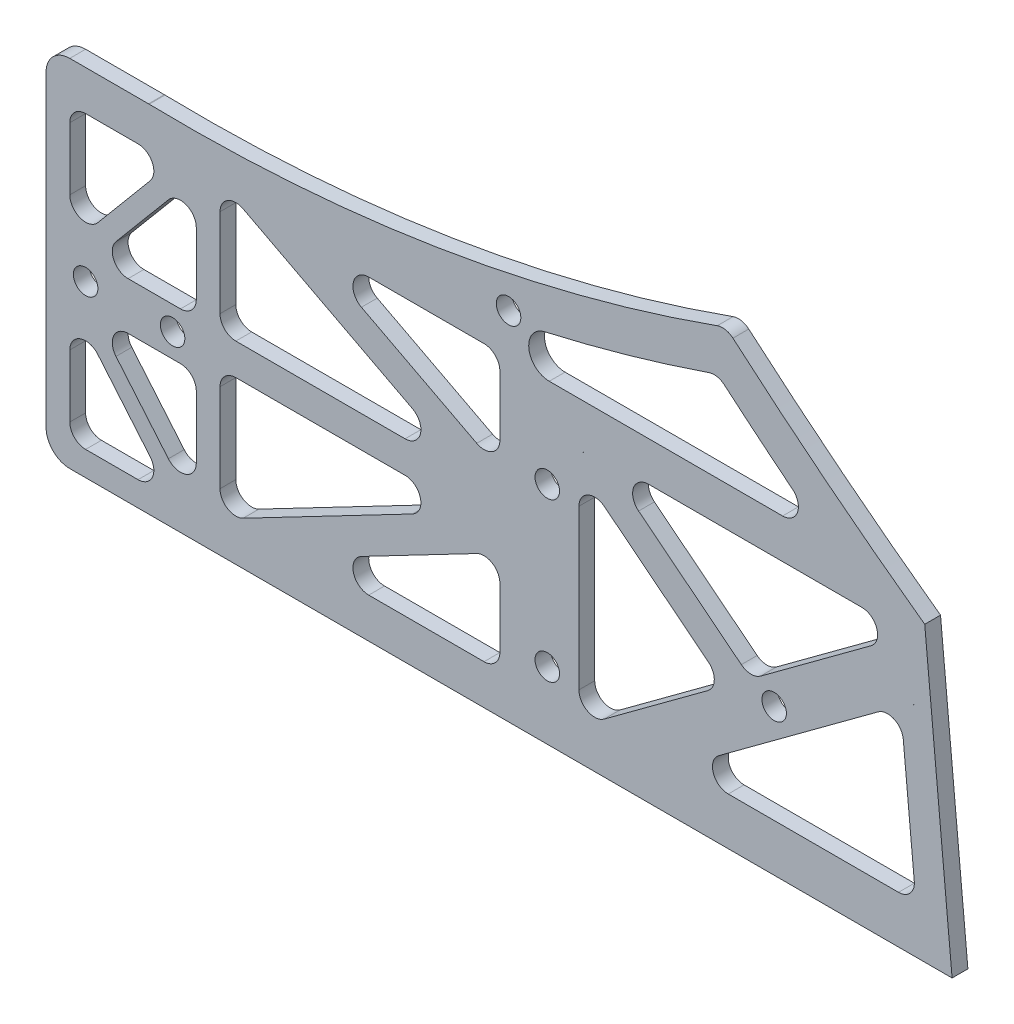
SolidWorks part; units mm, degrees
material "Thornel Mat VMA"
ref_plane "前视基准面" through (0, 0, 0) normal (0, 0, 1) x (1, 0, 0)
ref_plane "上视基准面" through (0, 0, 0) normal (0, 1, 0) x (1, 0, 0)
ref_plane "右视基准面" through (0, 0, 0) normal (1, 0, 0) x (0, 0, -1)
sketch "草图1" plane through (0, 0, 0) normal (0, 0, 1) x (1, 0, 0)
  line L1 (-82.5, -28.5) -> (82.5, -28.5)
  line L2 (-82.5, -28.5) -> (-82.5, 28.5)
  line L3 (-82.5, 28.5) -> (82.5, 28.5)
  line L4 (82.5, -28.5) -> (82.5, 28.5)
  line L5 (0, 28.5) -> (0, -28.5) construction
  line L6 (-82.5, 0) -> (82.5, 0) construction
  point P0 (0, 0)
  dimension "D1" = 57
  dimension "D2" = 165
extrude "凸台-拉伸1" add sketch "草图1" along normal blind 2
sketch "草图2" plane through (0, 0, 2) normal (0, 0, 1) x (1, 0, 0)
  line L0 (-82.5, 28.5) -> (-82.5, -28.5) construction
  line L1 (82.5, 28.5) -> (-82.5, 28.5) construction
  line L2 (82.5, -28.5) -> (82.5, 28.5) construction
  line L3 (-82.5, 16.5) -> (-82.5, 28.5)
  line L4 (-82.5, 28.5) -> (-7.5, 28.5)
  line L5 (-7.5, 28.5) -> (82.5, 28.5)
  line L6 (82.5, 28.5) -> (82.5, -28.5)
  arc A0 (-82.5, 16.5) -> (-7.5, 28.5) centre (-76.0232, 216.3951) ccw
  arc A1 (-7.5, 28.5) -> (82.5, -28.5) centre (222.5868, 292.2424) ccw
  dimension "D1" = 200
  dimension "D4" = 350
  dimension "D2" = 75
  dimension "D3" = 12
extrude "切除-拉伸1" cut sketch "草图2" against normal blind 6
sketch "草图3" [suppressed] plane through (0, 0, 41) normal (0, 0, 1) x (1, 0, 0)
  line L0 (-82.5, 16.5) -> (-82.5, -28.5) construction
  line L1 (-82.5, 13.4984) -> (-82.5, -28.5)
  line L2 (-82.5, -28.5) -> (72.8967, -28.5)
  line L3 (-82.5, -28.5) -> (82.5, -28.5) construction
  arc A2 (-82.5972, 13.5016) -> (-6.4722, 25.6816) centre (-76.0232, 216.3951) ccw
  arc A3 (-82.5, 13.4984) -> (-8.3642, 25.0021) centre (-76.0232, 216.3951) ccw
  arc A5 (-9.7222, 26.4846) -> (81.6278, -31.3704) centre (140.6454, 162.8612) ccw
  arc A6 (-8.3642, 25.0021) -> (72.8967, -28.5) centre (140.6454, 162.8612) ccw
  dimension "D1" = 3
  dimension "D2" = 3
extrude "切除-拉伸2" [suppressed] cut sketch "草图3" against normal blind 73
sketch "草图4" plane through (0, 0, 2) normal (0, 0, 1) x (1, 0, 0)
  line L0 (0, 0) -> (-77.5, 0) construction
  line L1 (-77.5, 0) -> (-77.5, -7) construction
  circle A1 centre (-77.5, -7) radius 1.55
  dimension "D3" = 3.1
  dimension "D1" = 77.5
  dimension "D2" = 7
extrude "切除-拉伸3" cut sketch "草图4" against normal blind 33
fillet "圆角1" [suppressed] radius 2
sketch "草图5" [suppressed] plane through (0, 0, 41) normal (0, 0, 1) x (1, 0, 0)
  circle A4 centre (-35, 16.5624) radius 4
  arc A6 (-82.5, 16.5) -> (-7.5, 28.5) centre (-76.0232, 216.3951) ccw construction
  dimension "D1" = 8
  dimension "D2" = 35
extrude "凸台-拉伸2" [suppressed] add sketch "草图5" against normal up to surface (41 mm away)
sketch "草图6" [suppressed] plane through (0, 0, 41) normal (0, 0, 1) x (1, 0, 0)
  circle A4 centre (40, -14.5832) radius 4
  arc A5 (-7.5, 28.5) -> (82.5, -28.5) centre (140.6454, 162.8612) ccw construction
  dimension "D1" = 8
  dimension "D2" = 40
extrude "凸台-拉伸3" [suppressed] add sketch "草图6" against normal up to surface (41 mm away)
sketch "草图7" [suppressed] plane through (0, 0, 0) normal (0, 0, -1) x (-1, 0, 0)
  circle A0 centre (35, 16.5624) radius 1.925
  circle A1 centre (-40, -14.5832) radius 1.925
  arc A2 (-43.8719, -15.5873) -> (-37.1511, -11.7753) centre (-40, -14.5832) ccw construction
  arc A3 (31.4241, 18.3549) -> (38.9929, 16.8011) centre (35, 16.5624) ccw construction
  dimension "D1" = 3.85
  dimension "D2" = 3.85
extrude "切除-拉伸4" [suppressed] cut sketch "草图7" against normal blind 50
sketch "草图8" plane through (0, 0, 2) normal (0, 0, 1) x (1, 0, 0)
  circle A0 centre (-1.4, -10) radius 1.55 construction
  circle A1 centre (-30.1, -20) radius 1.55 construction
  circle A2 centre (-30.1, 0) radius 1.55 construction
  circle A3 centre (-1.4, -10) radius 1.55
  circle A4 centre (-30.1, -20) radius 1.55
  circle A5 centre (-30.1, 0) radius 1.55
extrude "切除-拉伸5" cut sketch "草图8" against normal blind 10
fillet "圆角2" [suppressed] radius 3
chamfer "倒角1" [suppressed] distance 0.15 angle 45
sketch "草图9" plane through (0, 0, 0) normal (0, 0, -1) x (-1, 0, 0)
  circle A0 centre (-40, -14.5832) radius 2.075 construction
  circle A1 centre (35, 16.5624) radius 2.075 construction
  circle A2 centre (-40, -14.5832) radius 2.075 construction
  circle A3 centre (35, 16.5624) radius 2.075 construction
  circle A4 centre (35, 16.5624) radius 1.55
  circle A5 centre (-40, -14.5832) radius 1.55
  dimension "D1" = 3.1
extrude "切除-拉伸6" cut sketch "草图9" against normal blind 10
fillet "圆角3" radius 2 1 edges at (-7.5, 28.5, 1)
fillet "圆角4" radius 2 2 edges at (-82.5, -28.5, 1) (-82.5, 16.5, 1)
fillet "圆角5" [suppressed] radius 2
chamfer "倒角2" [suppressed] distance 1 angle 45
chamfer "倒角3" [suppressed] distance 1 angle 45
fillet "圆角6" [suppressed] radius 0.7
fillet "圆角7" [suppressed] radius 2
sketch "草图10" plane through (0, 0, 2) normal (0, 0, 1) x (1, 0, 0)
  line L1 (-29.8496, 11.3951) -> (5.4468, 11.3951)
  arc A0 (-80.4557, 16.4442) -> (-8.5997, 28.1026) centre (-76.0232, 216.3951) ccw construction
  arc A7 (-30.4279, 16.53) -> (-29.8496, 11.3951) centre (-29.8496, 13.9951) ccw
  arc A8 (-9.89, 23.9524) -> (80.4988, -33.082) centre (222.5868, 292.2424) ccw
  arc A9 (-8.5667, 22.8115) -> (5.4468, 11.3951) centre (222.5868, 292.2424) ccw
  arc A10 (-30.4279, 16.53) -> (-8.5667, 22.8115) centre (-76.0232, 216.3951) ccw
  dimension "D3" = 5.2
  dimension "D1" = 5
  dimension "D2" = 5
extrude "切除-拉伸7" cut sketch "草图10" against normal blind 10
fillet "圆角8" radius 2 2 edges at (5.4468, 11.3951, 1) (-8.5667, 22.8115, 1)
sketch "草图11" plane through (0, 0, 2) normal (0, 0, 1) x (1, 0, 0)
  line L0 (-71.5, 12.4442) -> (-71.5, -24.5)
  line L1 (-71.5, -24.5) -> (-36.1, -6.0279)
  line L2 (-36.1, -6.0279) -> (-71.5, 12.4442)
  line L3 (-36.1, -6.0279) -> (-71.5, -6.0279) construction
  line L4 (-80.5, -28.5) -> (82.5, -28.5) construction
  line L5 (-60.843, 11.3951) -> (-36.1, -1.5161)
  line L6 (-36.1, -1.5161) -> (-36.1, 11.3951)
  line L7 (-36.1, 11.3951) -> (-60.843, 11.3951)
  line L8 (-29.8496, 11.3951) -> (-0.3329, 11.3951) construction
  line L9 (-36.1, -4.0279) -> (-71.5, -4.0279)
  line L10 (-36.1, -8.0279) -> (-71.5, -8.0279)
  line L11 (-36.1, -4.0279) -> (-36.1, -8.0279)
  line L12 (-71.5, -4.0279) -> (-71.5, -8.0279)
  line L13 (-36.1, -10.5397) -> (-36.1, -23.4509)
  line L14 (-60.843, -23.4509) -> (-36.1, -10.5397)
  line L15 (-36.1, -23.4509) -> (-60.843, -23.4509)
  circle A1 centre (-77.5, -7) radius 1.55 construction
  circle A2 centre (-30.1, 0) radius 1.55 construction
  dimension "D2" = 4
  dimension "D3" = 6
  dimension "D1" = 4
  dimension "D4" = 6
  dimension "D5" = 4
  dimension "D6" = 2
  dimension "D7" = 2
extrude "切除-拉伸8" cut sketch "草图11" against normal blind 10 contours L15 L13 L14 | L1 L10 L0 | L9 L2 L0 | L6 L7 L5
fillet "圆角9" radius 2 12 edges at (-39.9328, -4.0279, 1) (-36.1, -10.5397, 1) (-36.1, -23.4509, 1) (-60.843, -23.4509, 1) (-36.1, -1.5161, 1) (-60.843, 11.3951, 1) (-36.1, 11.3951, 1) (-71.5, -24.5, 1) (-71.5, -8.0279, 1) (-39.9328, -8.0279, 1) (-71.5, -4.0279, 1) (-71.5, 12.4442, 1)
sketch "草图12" plane through (0, 0, 2) normal (0, 0, 1) x (1, 0, 0)
  line L0 (-26.1, 6.3951) -> (-26.1, -24.5)
  line L1 (-26.1, -24.5) -> (10.8729, 2.7859)
  line L2 (9.6853, 6.3951) -> (-26.1, 6.3951)
  line L3 (-29.8496, 11.3951) -> (-0.3329, 11.3951) construction
  line L4 (16.5197, -0.5038) -> (-13.2856, -22.5)
  line L5 (-13.2856, -22.5) -> (51.996, -22.5)
  line L6 (-80.5, -28.5) -> (82.5, -28.5) construction
  circle A0 centre (-30.1, 0) radius 1.55 construction
  circle A2 centre (-1.4, -10) radius 1.55 construction
  arc A3 (-6.6157, 27.7312) -> (82.5, -28.5) centre (222.5868, 292.2424) ccw construction
  arc A5 (10.8729, 2.7859) -> (9.6853, 6.3951) centre (9.6853, 4.3951) ccw
  arc A6 (16.5197, -0.5038) -> (51.996, -22.5) centre (222.5868, 292.2424) ccw
  dimension "D6" = 3
  dimension "D8" = 2
  dimension "D3" = 8
  dimension "D1" = 5
  dimension "D2" = 4
  dimension "D4" = 6
  dimension "D5" = 4
  dimension "D7" = 3
extrude "切除-拉伸9" cut sketch "草图12" against normal blind 10
fillet "圆角10" radius 2 5 edges at (-26.1, 6.3951, 1) (51.996, -22.5, 1) (16.5197, -0.5038, 1) (-13.2856, -22.5, 1) (-26.1, -24.5, 1)
sketch "草图13" plane through (0, 0, 2) normal (0, 0, 1) x (1, 0, 0)
  line L0 (-25.5142, 5.8093) -> (-6.0197, -9.6808) construction
  line L1 (-22.9124, -22.1476) -> (10.8729, 2.7859) construction
  line L6 (-26.7584, 4.2435) -> (-7.264, -11.2467)
  line L7 (-24.27, 7.3752) -> (-4.3529, -8.4508)
  line L8 (-26.7584, 4.2435) -> (-24.27, 7.3752)
  line L10 (-24.27, 7.3752) -> (-4.7755, -8.115) construction
  line L11 (-4.3529, -8.4508) -> (-7.264, -11.2467)
  arc A1 (-24.1, 6.3951) -> (-26.1, 4.3951) centre (-24.1, 4.3951) ccw construction
  dimension "D1" = 2
  dimension "D2" = 2
extrude "凸台-拉伸4" add sketch "草图13" against normal up to surface (2 mm away) up to face at (23.4152, -14.3272, 0)
fillet "圆角11" radius 2 4 edges at (-26.1, 3.7203, 1) (-23.0366, 6.3951, 1) (-4.3529, -8.4508, 1) (-7.6865, -10.9109, 1)
sketch "草图14" plane through (0, 0, 2) normal (0, 0, 1) x (1, 0, 0)
  line L0 (16.5234, -0.9675) -> (18.5379, -22.5) construction
  line L1 (-7.2074, -22.5) -> (44.2832, -22.5) construction
  line L2 (14.5321, -1.1538) -> (16.5466, -22.6863)
  line L3 (18.5147, -0.7812) -> (20.5466, -22.5)
  line L4 (14.5321, -1.1538) -> (18.5147, -0.7812)
  line L6 (18.5147, -0.7812) -> (20.5292, -22.3137) construction
  line L7 (20.5466, -22.5) -> (16.5466, -22.6863)
  arc A1 (17.6945, -1.3272) -> (15.3622, -1.3581) centre (16.5498, -2.9673) ccw construction
  dimension "D1" = 2
  dimension "D2" = 2
extrude "凸台-拉伸5" add sketch "草图14" against normal up to surface (2 mm away) up to face at (-19.6149, -10.6152, 0)
fillet "圆角12" radius 2 4 edges at (16.5292, -22.5, 1) (14.6036, -1.9179, 1) (18.6264, -1.9755, 1) (20.5466, -22.5, 1)
sketch "草图15" plane through (0, 0, 2) normal (0, 0, 1) x (1, 0, 0)
  line L0 (20.3769, -20.6863) -> (19.0235, -6.2202) construction
  line L1 (20.3769, -20.6863) -> (19.0235, -6.2202) construction
  line L2 (21.108, -28.5) -> (17.6445, 8.5195)
  line L3 (-80.5, -28.5) -> (82.5, -28.5) construction
  line L4 (21.108, -28.5) -> (82.5, -28.5)
  arc A0 (-6.6157, 27.7312) -> (82.5, -28.5) centre (222.5868, 292.2424) ccw construction
  arc A1 (17.6445, 8.5195) -> (82.5, -28.5) centre (222.5868, 292.2424) ccw
extrude "切除-拉伸10" cut sketch "草图15" against normal blind 10
sketch "草图16" [suppressed] plane through (0, 0, 41) normal (0, 0, 1) x (1, 0, 0)
  line L1 (15.7533, 2.827) -> (15.4673, 6.8791)
  line L6 (73.2412, -28.5) -> (82.5, -28.5)
  line L7 (-81.7419, 16.2581) -> (-82.295, 15.705)
  line L8 (-82.5, 15.2101) -> (-82.5, 14.8089)
  line L9 (-82.3105, 14.33) -> (-81.7028, 13.6822)
  line L10 (73.2412, -28.5) -> (82.5, -28.5)
  arc A0 (-7.478, 24.0503) -> (34.7696, -10.3419) centre (140.6454, 162.8612) ccw construction
  arc A19 (46.3243, -16.8957) -> (72.5705, -28.3842) centre (140.6454, 162.8612) ccw
  arc A20 (72.5705, -28.3842) -> (73.2412, -28.5) centre (73.2412, -26.5) ccw
  arc A21 (-6.6043, 27.519) -> (82.5, -28.5) centre (140.6454, 162.8612) ccw
  arc A22 (-6.6043, 27.519) -> (-8.7495, 28.049) centre (-8.0768, 26.1655) ccw
  arc A23 (-81.2287, 16.4629) -> (-8.7495, 28.049) centre (-76.0232, 216.3951) ccw
  arc A24 (-81.2287, 16.4629) -> (-81.7419, 16.2581) centre (-81.247, 15.7631) ccw
  arc A25 (-82.295, 15.705) -> (-82.5, 15.2101) centre (-81.8, 15.2101) ccw
  arc A26 (-82.5, 14.8089) -> (-82.3105, 14.33) centre (-81.8, 14.8089) ccw
  arc A27 (-81.7028, 13.6822) -> (-81.2102, 13.4614) centre (-81.1923, 14.1612) ccw
  arc A28 (-81.2102, 13.4614) -> (-41.7292, 16.3128) centre (-76.0232, 216.3951) ccw
  arc A29 (-38.5557, 14.7301) -> (-41.7292, 16.3128) centre (-41.2224, 13.3559) ccw
  arc A30 (-38.5557, 14.7301) -> (-31.01, 16.2792) centre (-35, 16.5624) ccw
  arc A31 (-28.7167, 18.9841) -> (-31.01, 16.2792) centre (-28.0176, 16.0667) ccw
  arc A32 (-28.7167, 18.9841) -> (-9.5918, 24.5726) centre (-76.0232, 216.3951) ccw
  arc A33 (-7.478, 24.0503) -> (-9.5918, 24.5726) centre (-8.9373, 22.6827) ccw
  arc A34 (-7.478, 24.0503) -> (34.7696, -10.3419) centre (140.6454, 162.8612) ccw
  arc A35 (36.1171, -13.6222) -> (34.7696, -10.3419) centre (33.205, -12.9016) ccw
  arc A36 (36.1171, -13.6222) -> (42.8174, -17.4226) centre (40, -14.5832) ccw
  arc A37 (46.3243, -16.8957) -> (42.8174, -17.4226) centre (44.9304, -19.5522) ccw
  arc A38 (46.3243, -16.8957) -> (72.5705, -28.3842) centre (140.6454, 162.8612) ccw
  arc A39 (72.5705, -28.3842) -> (73.2412, -28.5) centre (73.2412, -26.5) ccw
  arc A40 (15.4673, 6.8791) -> (82.5, -28.5) centre (140.6454, 162.8612) ccw
  arc A53 (15.7533, 2.827) -> (34.7696, -10.3419) centre (140.6454, 162.8612) ccw
  arc A54 (36.1171, -13.6222) -> (34.7696, -10.3419) centre (33.205, -12.9016) ccw
  arc A55 (36.1171, -13.6222) -> (42.8174, -17.4226) centre (40, -14.5832) ccw
  arc A56 (46.3243, -16.8957) -> (42.8174, -17.4226) centre (44.9304, -19.5522) ccw
  dimension "D1" = 0
extrude "切除-拉伸11" [suppressed] cut sketch "草图16" against normal through all
sketch "草图17" plane through (0, 0, 2) normal (0, 0, 1) x (1, 0, 0)
  line L0 (-80.4557, 16.4442) -> (-93.5, 16.4442)
  line L1 (-93.5, 16.4442) -> (-93.5, -28.5)
  line L2 (-93.5, -28.5) -> (-80.4429, -28.5)
  line L3 (-80.5, -28.5) -> (21.108, -28.5) construction
  line L4 (-82.5, 14.4447) -> (-82.5, -26.5) construction
  line L5 (-80.4557, 16.4442) -> (-80.4429, -28.5)
  dimension "D1" = 11
extrude "凸台-拉伸6" add sketch "草图17" against normal blind 2
fillet "圆角13" radius 3 2 edges at (-93.5, -28.5, 1) (-93.5, 16.4442, 1)
sketch "草图18" plane through (0, 0, 2) normal (0, 0, 1) x (1, 0, 0)
  line L0 (-77.5, -7) -> (-93.5, -7) construction
  line L1 (-93.5, 13.4442) -> (-93.5, -25.5) construction
  line L2 (-74.5, -4) -> (-87.418, -4)
  line L3 (-87.418, -4) -> (-74.5, 11.3951)
  line L4 (-74.5, 11.3951) -> (-74.5, -4)
  line L5 (-90.5, 11.3951) -> (-90.5, -4)
  line L6 (-90.5, -4) -> (-77.582, 11.3951)
  line L7 (-77.582, 11.3951) -> (-90.5, 11.3951)
  line L8 (-38.1, 11.3951) -> (-52.6869, 11.3951) construction
  line L9 (-71.5, 9.1447) -> (-71.5, -2.0279) construction
  line L10 (-87.418, -10) -> (-74.5, -25.3951)
  line L11 (-74.5, -10) -> (-87.418, -10)
  line L12 (-74.5, -25.3951) -> (-74.5, -10)
  line L13 (-90.5, -10) -> (-77.582, -25.3951)
  line L14 (-90.5, -25.3951) -> (-90.5, -10)
  line L15 (-77.582, -25.3951) -> (-90.5, -25.3951)
  circle A0 centre (-88.5, -7) radius 1.55
  circle A1 centre (-77.5, -7) radius 1.55 construction
  dimension "D1" = 5
  dimension "D2" = 3
  dimension "D3" = 50
  dimension "D4" = 3
  dimension "D5" = 3
extrude "切除-拉伸12" cut sketch "草图18" against normal blind 2
fillet "圆角14" radius 2 12 edges at (-77.582, -25.3951, 1) (-74.5, -25.3951, 1) (-74.5, -10, 1) (-90.5, -25.3951, 1) (-90.5, -10, 1) (-87.418, -10, 1) (-74.5, 11.3951, 1) (-74.5, -4, 1) (-87.418, -4, 1) (-90.5, -4, 1) (-77.582, 11.3951, 1) (-90.5, 11.3951, 1)
sketch "草图19" [suppressed] plane through (0, 0, 0) normal (0, 0, -1) x (-1, 0, 0)
  line L0 (81.2287, 16.4629) -> (93.2102, 16.4629)
  line L1 (93.2102, 16.4629) -> (93.2102, 13.4614)
  line L2 (93.2102, 13.4614) -> (81.2102, 13.4614)
  line L3 (81.2102, 13.4614) -> (81.2287, 16.4629)
  arc A1 (81.2102, 13.4614) -> (81.7028, 13.6822) centre (81.1923, 14.1612) ccw construction
  arc A2 (41.7292, 16.3128) -> (81.2102, 13.4614) centre (76.0232, 216.3951) ccw construction
  dimension "D1" = 12
extrude "凸台-拉伸7" [suppressed] add sketch "草图19" against normal up to surface (41 mm away)
chamfer "倒角4" [suppressed] distance 1
fillet "圆角15" [suppressed] radius 1
